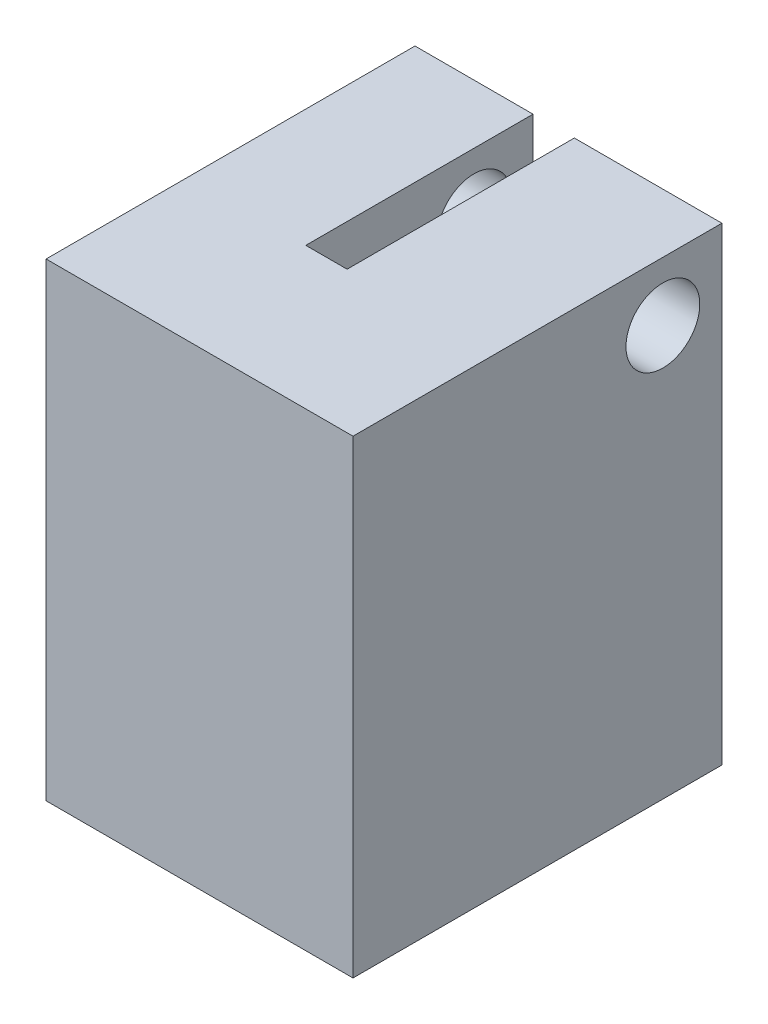
SolidWorks part; units mm, degrees
ref_plane "Front Plane" through (0, 0, 0) normal (0, 0, 1) x (1, 0, 0)
ref_plane "Top Plane" through (0, 0, 0) normal (0, 1, 0) x (1, 0, 0)
ref_plane "Right Plane" through (0, 0, 0) normal (1, 0, 0) x (0, 0, -1)
sketch "Sketch1" plane through (0, 0, 0) normal (1, 0, 0) x (0, 0, -1)
  line L1 (0, 20.193) -> (15.875, 20.193)
  line L2 (0, 20.193) -> (0, 0)
  line L3 (0, 0) -> (15.875, 0)
  line L4 (15.875, 20.193) -> (15.875, 0)
  circle A0 centre (13.335, 17.653) radius 1.5875
  dimension "D2" = 2.54
  dimension "D3" = 2.54
  dimension "D4" = 17.653
  dimension "D5" = 3.175
  dimension "D1" = 13.335
extrude "Boss-Extrude1" add sketch "Sketch1" along normal blind 13.208
sketch "Sketch4" plane through (0, 0, -15.875) normal (0, 0, -1) x (-1, 0, 0)
  line L0 (-13.208, 0) -> (0, 0) construction
  line L1 (-6.858, 20.193) -> (-5.08, 20.193)
  line L2 (-6.858, 20.193) -> (-6.858, 0)
  line L3 (-6.858, 0) -> (-5.08, 0)
  line L4 (-5.08, 20.193) -> (-5.08, 0)
  line L5 (-13.208, 20.193) -> (0, 20.193) construction
  line L6 (0, 0) -> (0, 20.193) construction
  dimension "D1" = 1.778
  dimension "D2" = 5.08
extrude "Cut-Extrude1" cut sketch "Sketch4" against normal offset from surface (9.779 mm away) 6.096 up to face at (6.604, 10.0965, 0)
